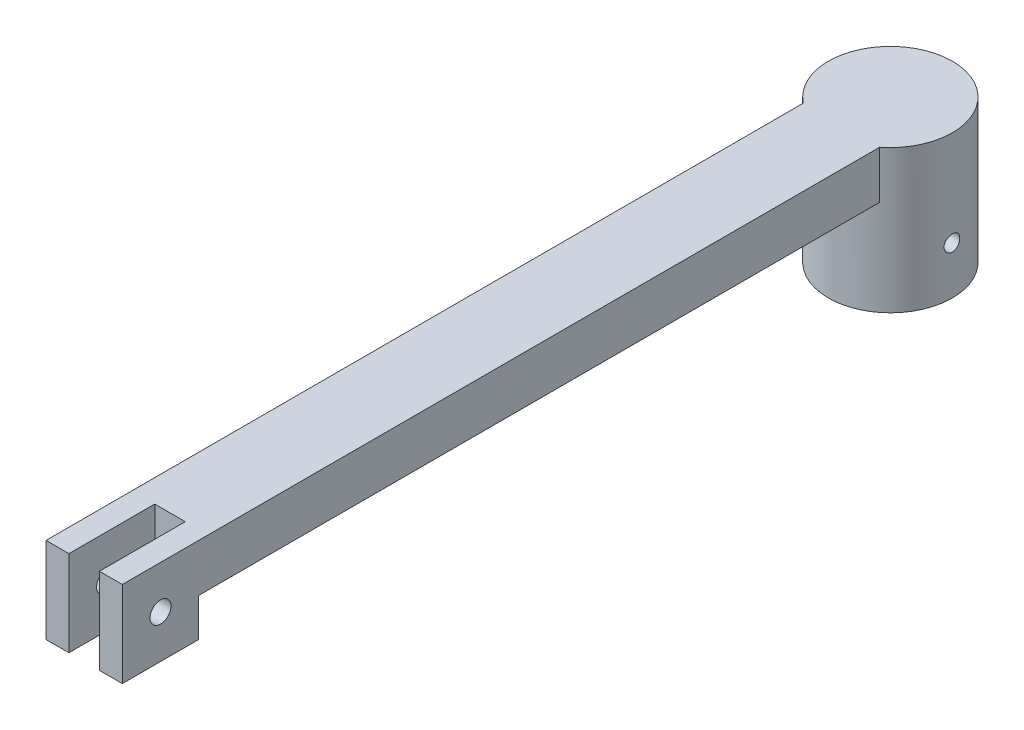
SolidWorks part; units mm, degrees
ref_plane "Front Plane" through (0, 0, 0) normal (0, 0, 1) x (1, 0, 0)
ref_plane "Top Plane" through (0, 0, 0) normal (0, 1, 0) x (1, 0, 0)
ref_plane "Right Plane" through (0, 0, 0) normal (1, 0, 0) x (0, 0, -1)
sketch "Croquis_zocalo" plane through (0, 0, 0) normal (0, 1, 0) x (1, 0, 0)
  circle A0 centre (0, 0) radius 13
  dimension "D1" = 26
extrude "Zocalo" add sketch "Croquis_zocalo" along normal blind 30
sketch "Croquis_zocalo_hueco" plane through (0, 0, 0) normal (0, 1, 0) x (1, 0, 0)
  circle A0 centre (0, 0) radius 8.2
  dimension "D1" = 16.4
extrude "Zocalo_hueco" cut sketch "Croquis_zocalo_hueco" along normal blind 27
ref_plane "Plano_Top Plane_+20" through (0, 20, 0) normal (0, 1, 0) x (1, 0, 0)
sketch "Croquis_barra" plane through (0, 20, 0) normal (0, 1, 0) x (1, 0, 0)
  line L1 (-8, -155) -> (8, -155)
  line L2 (-8, -155) -> (-8, 0)
  line L3 (-8, 0) -> (8, 0)
  line L4 (8, -155) -> (8, 0)
  line L5 (-8, -155) -> (8, 0) construction
  line L6 (-8, 0) -> (8, -155) construction
  dimension "D1" = 16
  dimension "D2" = 155
extrude "Barra" add sketch "Croquis_barra" along normal blind 10
ref_plane "Plano_Top Plane_+12" through (0, 12, 0) normal (0, 1, 0) x (1, 0, 0)
sketch "Croquis_horquilla" plane through (0, 12, 0) normal (0, 1, 0) x (1, 0, 0)
  line L0 (8, -155) -> (8, -10.247) construction
  line L1 (-8, -169) -> (8, -169)
  line L2 (-8, -169) -> (-8, -153)
  line L3 (-8, -153) -> (8, -153)
  line L4 (8, -169) -> (8, -153)
  line L5 (-8, -169) -> (8, -153) construction
  line L6 (-8, -153) -> (8, -169) construction
  point P0 (0, -161)
  dimension "D1" = 16
  dimension "D2" = 16
extrude "Horquilla" add sketch "Croquis_horquilla" along normal blind 18
sketch "Croquis_horquilla_ranura" plane through (0, 0, 0) normal (0, 1, 0) x (1, 0, 0)
  line L1 (-3.2, -171) -> (3.2, -171)
  line L2 (-3.2, -171) -> (-3.2, -151)
  line L3 (-3.2, -151) -> (3.2, -151)
  line L4 (3.2, -171) -> (3.2, -151)
  line L5 (-3.2, -171) -> (3.2, -151) construction
  line L6 (-3.2, -151) -> (3.2, -171) construction
  dimension "D1" = 6.4
  dimension "D2" = 20
extrude "Horquilla_ranura" cut sketch "Croquis_horquilla_ranura" along normal through all and the other way through all
sketch "Croquis_ejes" plane through (0, 0, 0) normal (1, 0, 0) x (0, 0, -1)
  circle A0 centre (-161, 21) radius 2.2
  circle A1 centre (0, 10) radius 1.65
  dimension "D1" = 4.4
  dimension "D2" = 3.3
extrude "Eje_camara_y_prisionero" cut sketch "Croquis_ejes" along normal through all and the other way through all
